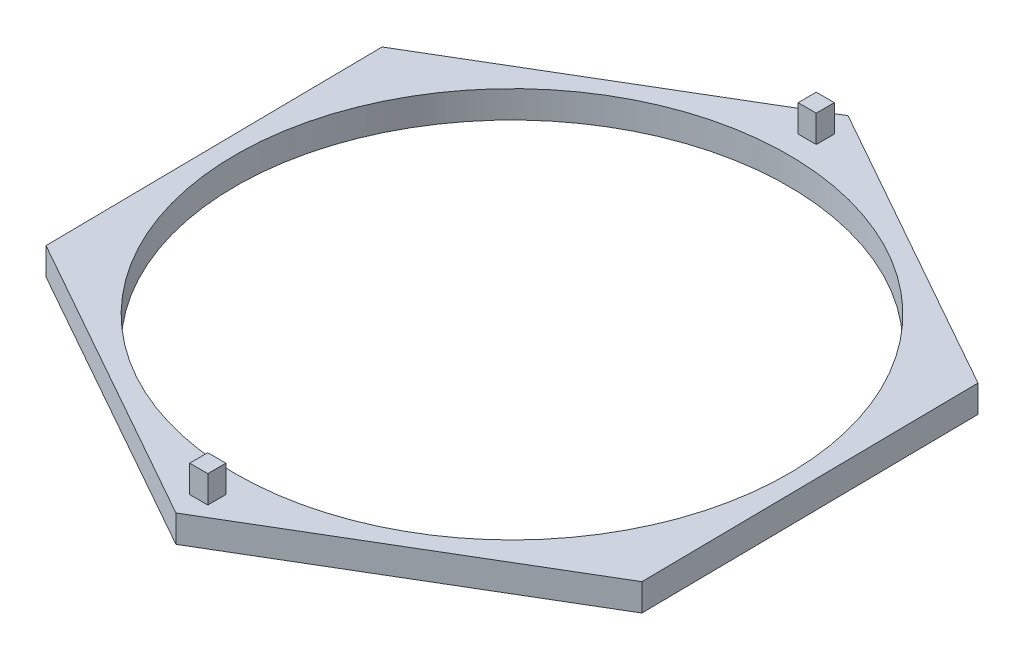
SolidWorks part; units mm, degrees
ref_plane "Front Plane" through (0, 0, 0) normal (0, 0, 1) x (1, 0, 0)
ref_plane "Top Plane" through (0, 0, 0) normal (0, 1, 0) x (1, 0, 0)
ref_plane "Right Plane" through (0, 0, 0) normal (1, 0, 0) x (0, 0, -1)
sketch "Sketch1" plane through (0, 0, 0) normal (0, 1, 0) x (1, 0, 0)
  line L1 (-32.7184, 18.3804) -> (-32.2771, -19.1448)
  line L2 (-32.2771, -19.1448) -> (0.4413, -37.5252)
  line L3 (0.4413, -37.5252) -> (32.7184, -18.3804)
  line L4 (32.7184, -18.3804) -> (32.2771, 19.1448)
  line L5 (32.2771, 19.1448) -> (-0.4413, 37.5252)
  line L6 (-0.4413, 37.5252) -> (-32.7184, 18.3804)
  circle A0 centre (0, 0) radius 32.5 construction
  dimension "D1" = 65
extrude "Boss-Extrude1" add sketch "Sketch1" along normal blind 3
sketch "Sketch2" plane through (0, 3, 0) normal (0, 1, 0) x (1, 0, 0)
  circle A0 centre (0, 0) radius 30.5
  dimension "D1" = 61
extrude "Cut-Extrude1" cut sketch "Sketch2" against normal through all
sketch "Sketch3" plane through (0, 3, 0) normal (0, 1, 0) x (1, 0, 0)
  line L0 (-0.4413, 37.5252) -> (-0.4413, 30.4968) construction
  line L2 (0.5587, 35.011) -> (-1.4413, 35.011)
  line L3 (0.5587, 35.011) -> (0.5587, 33.011)
  line L4 (0.5587, 33.011) -> (-1.4413, 33.011)
  line L5 (-1.4413, 35.011) -> (-1.4413, 33.011)
  line L6 (0.5587, 35.011) -> (-1.4413, 33.011) construction
  line L7 (0.5587, 33.011) -> (-1.4413, 35.011) construction
  circle A0 centre (0, 0) radius 30.5 construction
  point P5 (-0.4413, 34.011)
  dimension "D1" = 2
  dimension "D2" = 2
extrude "Boss-Extrude2" add sketch "Sketch3" along normal blind 3
sketch "Sketch4" plane through (0, 3, 0) normal (0, 1, 0) x (1, 0, 0)
  line L0 (0.4413, -37.5252) -> (0.4413, -30.4968) construction
  line L2 (1.4413, -35.011) -> (-0.5587, -35.011)
  line L3 (1.4413, -35.011) -> (1.4413, -33.011)
  line L4 (1.4413, -33.011) -> (-0.5587, -33.011)
  line L5 (-0.5587, -35.011) -> (-0.5587, -33.011)
  line L6 (1.4413, -35.011) -> (-0.5587, -33.011) construction
  line L7 (1.4413, -33.011) -> (-0.5587, -35.011) construction
  circle A0 centre (0, 0) radius 30.5 construction
  point P5 (0.4413, -34.011)
  dimension "D1" = 2
  dimension "D2" = 2
extrude "Boss-Extrude3" add sketch "Sketch4" along normal blind 3
